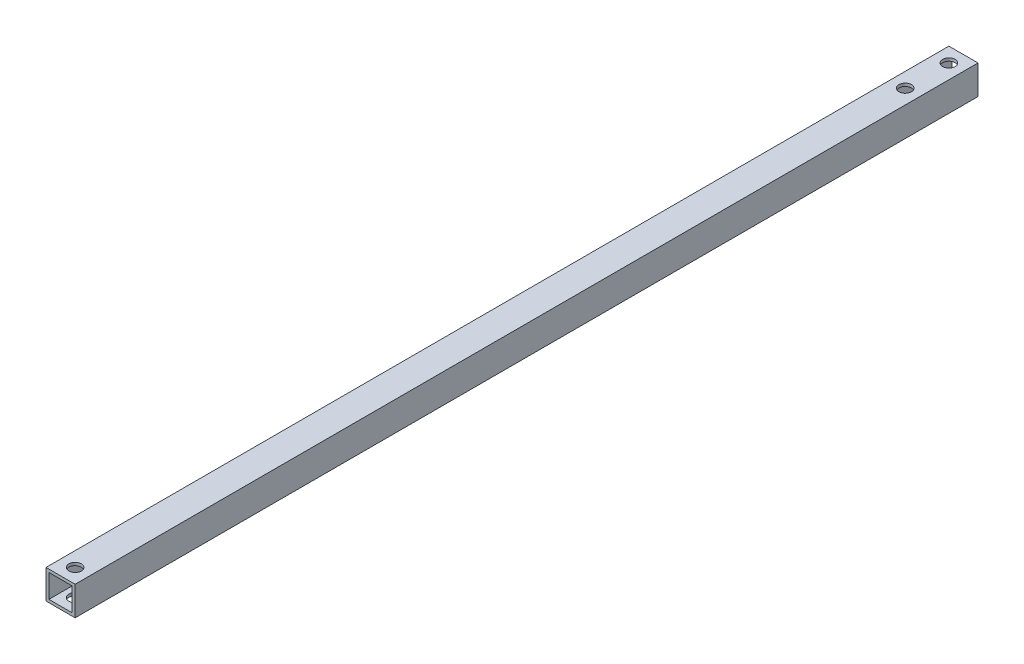
SolidWorks part; units mm, degrees
material "5052-H34"
ref_plane "正面" through (0, 0, 0) normal (0, 0, 1) x (1, 0, 0)
ref_plane "平面" through (0, 0, 0) normal (0, 1, 0) x (1, 0, 0)
ref_plane "右側面" through (0, 0, 0) normal (1, 0, 0) x (0, 0, -1)
sketch "ｽｹｯﾁ2" plane through (0, 0, 0) normal (0, 0, 1) x (1, 0, 0)
  line L1 (0, 0) -> (10, 0)
  line L2 (0, 0) -> (0, 10)
  line L3 (0, 10) -> (10, 10)
  line L4 (10, 0) -> (10, 10)
  dimension "D1" = 10
  dimension "D2" = 10
extrude "押し出し-薄板1" add sketch "ｽｹｯﾁ2" along normal blind 310 thin thin type one direction reverse wall 1
sketch "ｽｹｯﾁ3" plane through (0, 10, 0) normal (0, 1, 0) x (1, 0, 0)
  line L0 (5, 0) -> (5, -310) construction
  line L1 (10, 0) -> (0, 0) construction
  line L2 (10, -310) -> (0, -310) construction
  line L3 (10, -155) -> (0, -155) construction
  line L4 (10, -310) -> (10, 0) construction
  line L5 (0, -310) -> (0, 0) construction
  circle A0 centre (5, -305) radius 2.15
  circle A1 centre (5, -5) radius 2.15
  circle A2 centre (5, -20) radius 2.15
  dimension "D1" = 4.3
  dimension "D2" = 5
  dimension "D3" = 15
extrude "ｶｯﾄ - 押し出し1" cut sketch "ｽｹｯﾁ3" against normal up to surface (10 mm away) up to face at (5, 0, 155)
equation "\"D1@押し出し-薄板1\"=sqr(213.5^2+108.5^2)+10.00mm"
